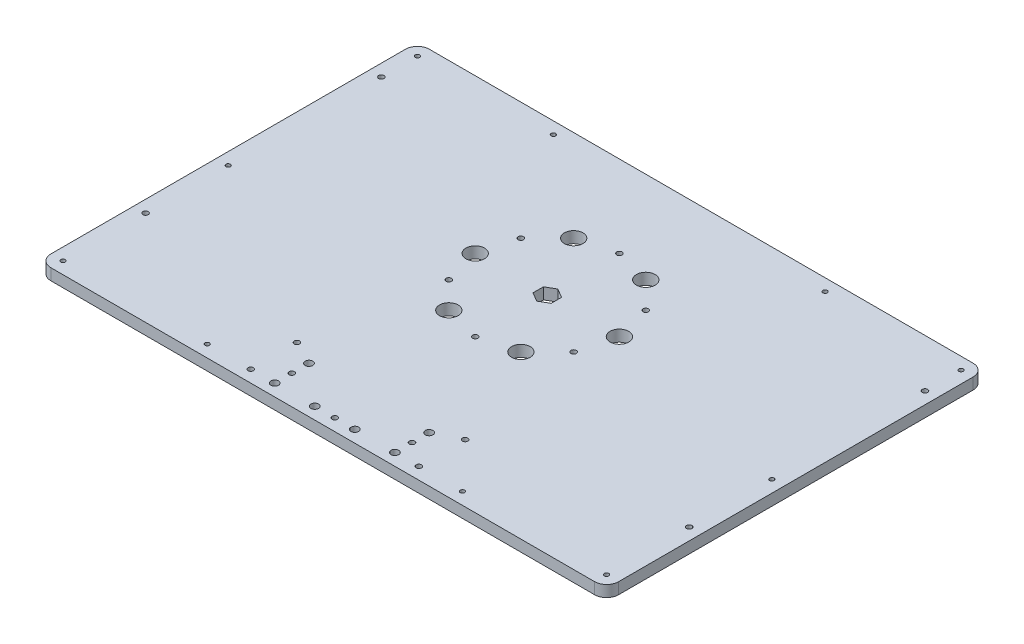
SolidWorks part; units mm, degrees
material "Balsa"
ref_plane "Front" through (0, 0, 0) normal (0, 0, 1) x (1, 0, 0)
ref_plane "Top" through (0, 0, 0) normal (0, 1, 0) x (1, 0, 0)
ref_plane "Right" through (0, 0, 0) normal (1, 0, 0) x (0, 0, -1)
sketch "Sketch1" plane through (0, 0, 0) normal (0, 1, 0) x (1, 0, 0)
  line L0 (150, 0) -> (150, 200) construction
  line L1 (0, 0) -> (300, 0)
  line L2 (0, 0) -> (0, 200)
  line L3 (0, 200) -> (300, 200)
  line L4 (300, 0) -> (300, 200)
  dimension "D2" = 300
  dimension "D6" = 200
extrude "Boss-Extrude1" add sketch "Sketch1" along normal blind 6
sketch "Sketch6" plane through (0, 6, 0) normal (0, 1, 0) x (1, 0, 0)
  line L0 (150, 118.651) -> (150, 0) construction
  line L1 (0, 0) -> (300, 0) construction
  circle A0 centre (150, 118.651) radius 2.5
  dimension "D1" = 5
  dimension "D2" = 118.651
extrude "Cut-Extrude2" cut sketch "Sketch6" against normal through all
fillet "Fillet1" radius 6.35 4 edges at (0, 3, 0) (300, 3, 0) (300, 3, -200) (0, 3, -200)
sketch "Sketch13" plane through (0, 6, 5.8) normal (0, 1, 0) x (1, 0, 0)
  line L0 (150, 5.8) -> (150, 205.8) construction
  line L1 (6.35, 5.8) -> (293.65, 5.8) construction
  line L2 (293.65, 205.8) -> (6.35, 205.8) construction
  line L3 (0, 199.45) -> (0, 12.15) construction
  line L4 (6.35, 99.4498) -> (6.35, 12.15) construction
  line L5 (6.35, 12.15) -> (82.55, 12.15) construction
  line L6 (82.55, 12.15) -> (82.55, 1.2299) construction
  line L22 (293.65, 12.15) -> (217.45, 12.15) construction
  line L23 (293.65, 99.4498) -> (293.65, 12.15) construction
  line L26 (150, 199.45) -> (78.175, 199.45) construction
  line L27 (78.175, 199.45) -> (6.35, 199.45) construction
  circle A0 centre (6.35, 199.45) radius 1.25
  circle A1 centre (78.175, 199.45) radius 1.25
  circle A2 centre (221.825, 199.45) radius 1.25
  circle A3 centre (293.65, 199.45) radius 1.25
  circle A4 centre (293.65, 99.4498) radius 1.25
  circle A5 centre (293.65, 12.15) radius 1.25
  circle A6 centre (217.45, 12.15) radius 1.25
  circle A7 centre (82.55, 12.15) radius 1.25
  circle A8 centre (6.35, 12.15) radius 1.25
  circle A9 centre (6.35, 99.4498) radius 1.25
  point P0 (6.35, 99.4498)
  point P1 (6.35, 12.15)
  point P10 (82.55, 12.15)
  point P71 (293.65, 99.4498)
  point P75 (217.45, 12.15)
  point P77 (293.65, 12.15)
  point P85 (6.35, 199.45)
  point P87 (78.175, 199.45)
  point P101 (221.825, 199.45)
  point P102 (293.65, 199.45)
  dimension "D2" = 76.2
  dimension "D7" = 2.5
  dimension "D1" = 6.35
  dimension "D3" = 6.35
  dimension "D4" = 6.35
  dimension "D5" = 6.35
  dimension "D6" = 87.2998
sketch "Sketch2" plane through (0, 6, 0) normal (0, 1, 0) x (1, 0, 0)
  line L0 (150, 49.9999) -> (150, 0) construction
  line L1 (6.35, 0) -> (293.65, 0) construction
  line L2 (0, 49.9999) -> (300, 49.9999) construction
  line L3 (0, 193.65) -> (0, 6.35) construction
  line L4 (150, 49.9999) -> (150, 99.9998) construction
  line L5 (50.8, 75.3999) -> (50.8, 49.9999) construction
  line L6 (300, 6.35) -> (300, 193.65) construction
  line L7 (0, 193.65) -> (0, 6.35) construction
  line L8 (293.65, 200) -> (6.35, 200) construction
  line L9 (150, 99.9998) -> (0, 99.9998) construction
  line L10 (0, 193.65) -> (0, 6.35) construction
  circle A0 centre (6.35, 174.6) radius 1.5
  circle A1 centre (6.35, 49.9999) radius 1.5
  circle A2 centre (249.2, 75.3999) radius 1.5 construction
  circle A3 centre (50.8, 75.3999) radius 1.5 construction
  circle A4 centre (293.65, 49.9999) radius 1.5
  circle A5 centre (50.8, 24.5999) radius 1.5 construction
  circle A6 centre (249.2, 24.5999) radius 1.5 construction
  circle A7 centre (25.4, 193.65) radius 1.5 construction
  circle A9 centre (293.65, 174.6) radius 1.5
  dimension "D1" = 3
  dimension "D8" = 25.4
  dimension "D9" = 25.4
  dimension "D2" = 6.35
  dimension "D3" = 25.4
  dimension "D4" = 50.8
  dimension "D5" = 99.9998
  dimension "D6" = 6.35
  dimension "D7" = 6.35
extrude "Cut-Extrude1" cut sketch "Sketch2" against normal through all
extrude "M3-tap" cut sketch "Sketch13" against normal through all
sketch "Sketch16" plane through (0, 6, -5.8) normal (0, -1, 0) x (1, 0, 0)
  line L0 (150, -112.851) -> (150, 0) construction
  line L3 (150, -25.001) -> (181.75, -25.001) construction
  line L4 (181.75, -25.001) -> (181.75, -0.551) construction
  line L6 (118.25, -0.551) -> (139.4167, -0.551) construction
  line L7 (139.4167, -0.551) -> (160.5833, -0.551) construction
  line L8 (160.5833, -0.551) -> (181.75, -0.551) construction
  circle A0 centre (150, -112.851) radius 80 construction
  circle A1 centre (150, -112.851) radius 2.5 construction
  circle A2 centre (150, -25.001) radius 7.85 construction
  circle A3 centre (150, -25.001) radius 6.35 construction
  circle A4 centre (118.25, -18.651) radius 2.1
  circle A5 centre (118.25, -0.551) radius 2.1
  circle A6 centre (139.4167, -0.551) radius 2.1
  circle A7 centre (160.5833, -0.551) radius 2.1
  circle A8 centre (181.75, -0.551) radius 2.1
  circle A9 centre (181.75, -18.651) radius 2.1
  point P0 (181.75, -0.551)
  point P28 (181.75, -18.651)
  point P32 (118.25, -18.651)
  point P33 (118.25, -0.551)
  point P34 (139.4167, -0.551)
  point P36 (160.5833, -0.551)
  dimension "D1" = 160
  dimension "D2" = 1.5
  dimension "D3" = 12.7
  dimension "D7" = 4.2
  dimension "D4" = 31.75
  dimension "D5" = 24.45
  dimension "D6" = 18.1
extrude "M5-tap2" cut sketch "Sketch16" along normal through all
sketch "Sketch9" plane through (0, 6, 0) normal (0, 1, 0) x (-1, 0, 0)
  line L0 (-118.25, -24.451) -> (-118.25, -6.351) construction
  line L1 (-118.25, -6.351) -> (-181.75, -6.351) construction
  line L2 (-181.75, -6.351) -> (-181.75, -24.451) construction
  circle A0 centre (-118.25, -15.401) radius 1.5
  circle A1 centre (-150, -6.351) radius 1.5
  circle A2 centre (-181.75, -15.401) radius 1.5
  dimension "D1" = 3
extrude "Cut-Extrude3" cut sketch "Sketch9" against normal through all
sketch "Sketch10" plane through (0, 6, 0) normal (0, 1, 0) x (1, 0, 0)
  line L0 (124.6, 75.5832) -> (124.6, 37.151) construction
  line L1 (124.6, 37.151) -> (92.85, 37.151) construction
  line L2 (92.85, 37.151) -> (92.85, 0) construction
  line L3 (6.35, 0) -> (293.65, 0) construction
  line L4 (92.85, 0) -> (207.15, 0) construction
  line L5 (207.15, 0) -> (207.15, 37.151) construction
  line L6 (207.15, 37.151) -> (175.4, 37.151) construction
  line L7 (175.4, 37.151) -> (175.4, 75.5832) construction
  line L8 (150, 118.651) -> (150, 156.751) construction
  line L9 (150, 118.651) -> (182.9956, 137.701) construction
  line L10 (150, 118.651) -> (182.9956, 99.601) construction
  line L11 (92.85, 30.801) -> (207.15, 30.801) construction
  line L12 (105.55, 30.801) -> (105.55, 6.35) construction
  line L13 (150, 0) -> (150, 30.801) construction
  circle A0 centre (150, 118.651) radius 80 construction
  arc A1 (175.4, 75.5832) -> (124.6, 75.5832) centre (150, 118.651) ccw construction
  circle A4 centre (150, 156.751) radius 1.5
  circle A5 centre (182.9956, 137.701) radius 1.5
  circle A6 centre (182.9956, 99.601) radius 1.5
  circle A7 centre (150, 80.551) radius 1.5
  circle A8 centre (117.0044, 99.601) radius 1.5
  circle A9 centre (117.0044, 137.701) radius 1.5
  circle A10 centre (105.55, 30.801) radius 1.5
  circle A11 centre (105.55, 6.35) radius 1.5
  circle A12 centre (194.45, 6.35) radius 1.5
  circle A13 centre (194.45, 30.801) radius 1.5
  circle A14 centre (181.75, 24.451) radius 2.1 construction
  circle A15 centre (118.25, 6.351) radius 2.1 construction
  dimension "D1" = 160
  dimension "D2" = 100
  dimension "D8" = 3
  dimension "D9" = 6.35
  dimension "D3" = 25.4
  dimension "D4" = 12.7
  dimension "D5" = 50.8
  dimension "D7" = 38.1
  dimension "D10" = 6.35
  dimension "D11" = 12.7
  dimension "D6" = 6
extrude "Cut-Extrude5" cut sketch "Sketch10" against normal through all
sketch "Sketch17" plane through (0, 6, 0) normal (0, 1, 0) x (1, 0, 0)
  line L0 (150, 118.651) -> (188.1, 118.651) construction
  line L1 (130.95, 151.6466) -> (150, 118.651) construction
  line L2 (150, 118.651) -> (169.05, 151.6466) construction
  circle A0 centre (188.1, 118.651) radius 5
  circle A1 centre (169.05, 85.6555) radius 5
  circle A2 centre (130.95, 85.6555) radius 5
  circle A3 centre (111.9, 118.651) radius 5
  circle A4 centre (130.95, 151.6466) radius 5
  circle A5 centre (169.05, 151.6466) radius 5
  dimension "D1" = 10
  dimension "D2" = 38.1
extrude "M3_counterbore" cut sketch "Sketch17" against normal through all
sketch "Sketch18" plane through (0, 6, 0) normal (0, 1, 0) x (1, 0, 0)
  line L0 (150, 118.651) -> (154.8, 118.651) construction
  line L1 (154.8, 121.4223) -> (154.8, 115.8797)
  line L2 (154.8, 115.8797) -> (150, 113.1085)
  line L3 (150, 113.1085) -> (145.2, 115.8797)
  line L4 (145.2, 115.8797) -> (145.2, 121.4223)
  line L5 (145.2, 121.4223) -> (150, 124.1936)
  line L6 (150, 124.1936) -> (154.8, 121.4223)
  line L7 (150, 118.651) -> (145.2, 118.651) construction
  dimension "D2" = 9.6
  dimension "D1" = 6
extrude "Cut-Extrude6" cut sketch "Sketch18" against normal through all
other "Move Face1" face at (111.9, 0, -113.651) face at (6.35, 0, -173.1) face at (6.35, 0, -48.4999) face at (293.65, 0, -51.4999) face at (293.65, 0, -176.1) face at (6.35, 0, -192.4) face at (78.175, 0, -192.4) face at (221.825, 0, -192.4) face at (293.65, 0, -192.4) face at (293.65, 0, -92.3998) face at (293.65, 0, -5.1) face at (217.45, 0, -5.1) face at (82.55, 0, -5.1) face at (6.35, 0, -5.1) face at (6.35, 0, -92.3998) face at (118.25, 0, -26.551) face at (118.25, 0, -8.451) face at (139.4167, 0, -8.451) face at (160.5833, 0, -8.451) face at (181.75, 0, -8.451) face at (181.75, 0, -26.551) face at (118.25, 0, -13.901) face at (150, 0, -4.851) face at (181.75, 0, -13.901) face at (150, 0, -155.251) face at (182.9956, 0, -136.201) face at (182.9956, 0, -98.101) face at (150, 0, -79.051) face at (117.0044, 0, -98.101) face at (117.0044, 0, -136.201) face at (105.55, 0, -29.301) face at (105.55, 0, -4.85) face at (194.45, 0, -7.85) face at (194.45, 0, -32.301) face at (188.1, 0, -113.651) face at (169.05, 0, -80.6555) face at (130.95, 0, -80.6555) face at (130.95, 0, -146.6466) face at (169.05, 0, -146.6466) parameters "D1"=0.08
